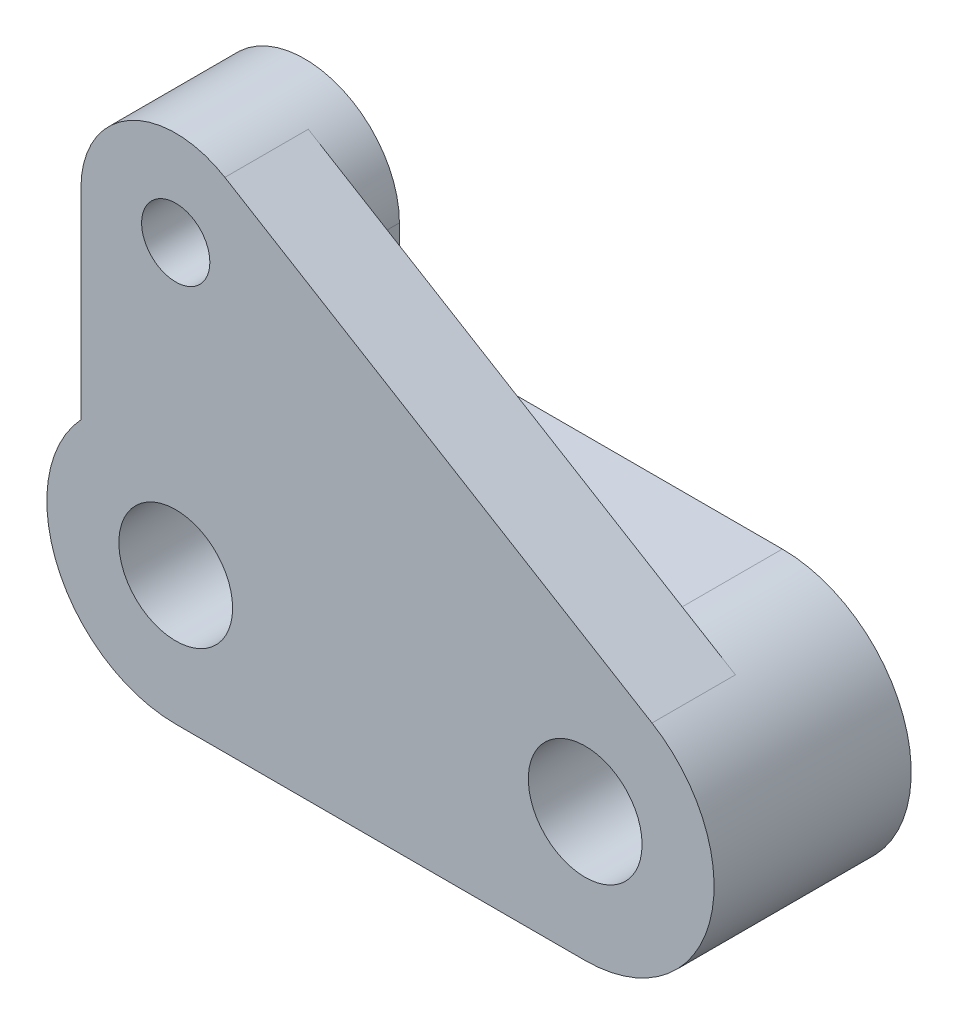
SolidWorks part; units mm, degrees
material "Hexcel AS4C (3000 Filaments)"
ref_plane "Front Plane" through (0, 0, 0) normal (0, 0, 1) x (1, 0, 0)
ref_plane "Top Plane" through (0, 0, 0) normal (0, 1, 0) x (1, 0, 0)
ref_plane "Right Plane" through (0, 0, 0) normal (1, 0, 0) x (0, 0, -1)
sketch "Sketch1" plane through (0, 0, 0) normal (0, 0, 1) x (1, 0, 0)
  line L0 (-54, 0) -> (54, 0) construction
  line L1 (-54, 34) -> (54, 34)
  line L2 (-54, -34) -> (54, -34)
  arc A0 (-54, 34) -> (-54, -34) centre (-54, 0) ccw
  arc A1 (54, -34) -> (54, 34) centre (54, 0) ccw
  point P3 (0, 0)
  dimension "D2" = 34
  dimension "D1" = 108
extrude "Boss-Extrude1" add sketch "Sketch1" along normal mid plane 52
sketch "Sketch2" plane through (0, 0, 26) normal (0, 0, 1) x (1, 0, 0)
  circle A0 centre (54, 0) radius 15
  circle A1 centre (-54, 0) radius 15
  arc A2 (54, -34) -> (54, 34) centre (54, 0) ccw construction
  arc A3 (-54, 34) -> (-54, -34) centre (-54, 0) ccw construction
  dimension "D1" = 30
extrude "Cut-Extrude1" cut sketch "Sketch2" against normal through all
sketch "Sketch3" plane through (0, 0, 26) normal (0, 0, 1) x (1, 0, 0)
  circle A0 centre (-54, 76) radius 25
  circle A1 centre (-54, 76) radius 9
  circle A3 centre (-54, 0) radius 15 construction
  point P0 (0, 0)
  point P4 (0, 0)
  dimension "D1" = 50
  dimension "D2" = 18
  dimension "D3" = 76
extrude "Boss-Extrude2" add sketch "Sketch3" against normal blind 34 separate body
sketch "Sketch4" plane through (0, 0, 26) normal (0, 0, 1) x (1, 0, 0)
  line L0 (-79, 76) -> (-79, 23.0434)
  line L1 (-29, 76) -> (-29, 34)
  line L2 (54, 34) -> (-54, 34) construction
  line L3 (-29, 34) -> (-54, 34)
  circle A0 centre (-54, 76) radius 25 construction
  arc A1 (-54, 34) -> (-54, -34) centre (-54, 0) ccw construction
  arc A2 (-79, 76) -> (-29, 76) centre (-54, 76) ccw
  arc A3 (-54, 34) -> (-79, 23.0434) centre (-54, 0) ccw
extrude "Boss-Extrude3" add sketch "Sketch4" against normal blind 34
fillet "Fillet1" radius 15 1 edges at (-29, 34, 9)
sketch "Sketch5" plane through (0, 0, 26) normal (0, 0, 1) x (1, 0, 0)
  line L0 (-41.0395, 97.3781) -> (71.6263, 29.0743)
  line L4 (54, 34) -> (-14, 34)
  line L5 (-29, 49) -> (-29, 76)
  line L6 (-79, 76) -> (-79, 23.0434)
  line L7 (-54, -34) -> (54, -34)
  line L8 (54, 34) -> (-14, 34)
  line L9 (-29, 49) -> (-29, 76)
  arc A4 (-29, 49) -> (-14, 34) centre (-14, 49) ccw
  arc A5 (-29, 76) -> (-79, 76) centre (-54, 76) ccw
  arc A6 (-79, 23.0434) -> (-54, -34) centre (-54, 0) ccw
  arc A7 (54, -34) -> (54, 34) centre (54, 0) ccw
  arc A8 (-29, 49) -> (-14, 34) centre (-14, 49) ccw
  arc A9 (-29, 76) -> (-41.0395, 97.3781) centre (-54, 76) ccw
  arc A11 (71.6263, 29.0743) -> (54, 34) centre (54, 0) ccw
  dimension "D1" = 0
extrude "Boss-Extrude4" add sketch "Sketch5" against normal blind 22 contours L0 A11 L8 A8 L9 A9
